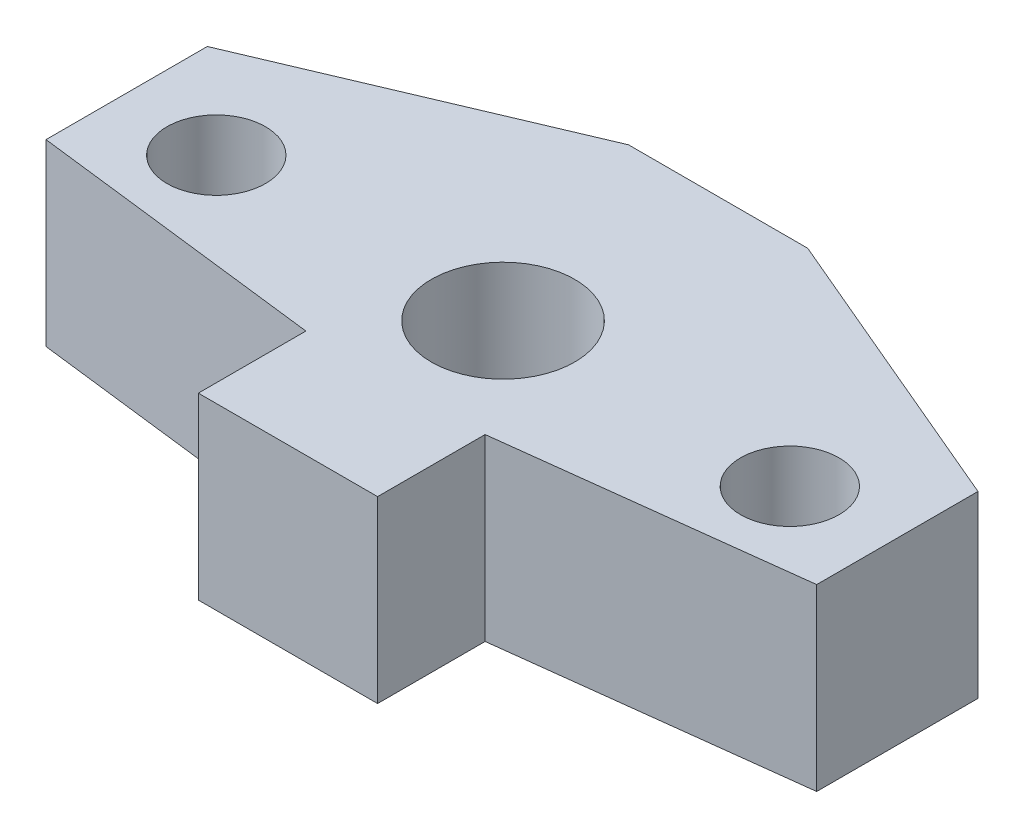
SolidWorks part; units mm, degrees
ref_plane "Спереди" through (0, 0, 0) normal (0, 0, 1) x (1, 0, 0)
ref_plane "Сверху" through (0, 0, 0) normal (0, 1, 0) x (1, 0, 0)
ref_plane "Справа" through (0, 0, 0) normal (1, 0, 0) x (0, 0, -1)
sketch "Эскиз1" plane through (0, 0, 0) normal (0, 1, 0) x (1, 0, 0)
  line L1 (16.5, 0) -> (26.5, 0)
  line L2 (0, 8) -> (0, 17)
  line L3 (16.5, 24) -> (26.5, 24)
  line L4 (43, 8) -> (43, 17)
  line L6 (43, 17) -> (26.5, 24)
  line L7 (16.5, 0) -> (16.5, 6)
  line L8 (16.5, 24) -> (0, 17)
  line L9 (26.5, 0) -> (26.5, 6)
  line L10 (16.5, 6) -> (0, 8)
  line L11 (26.5, 6) -> (43, 8)
  circle A0 centre (5.5, 12) radius 2.75
  circle A1 centre (37.5, 12) radius 2.75
  circle A2 centre (21.5, 12) radius 4
extrude "Бобышка-Вытянуть1" add sketch "Эскиз1" along normal blind 10
